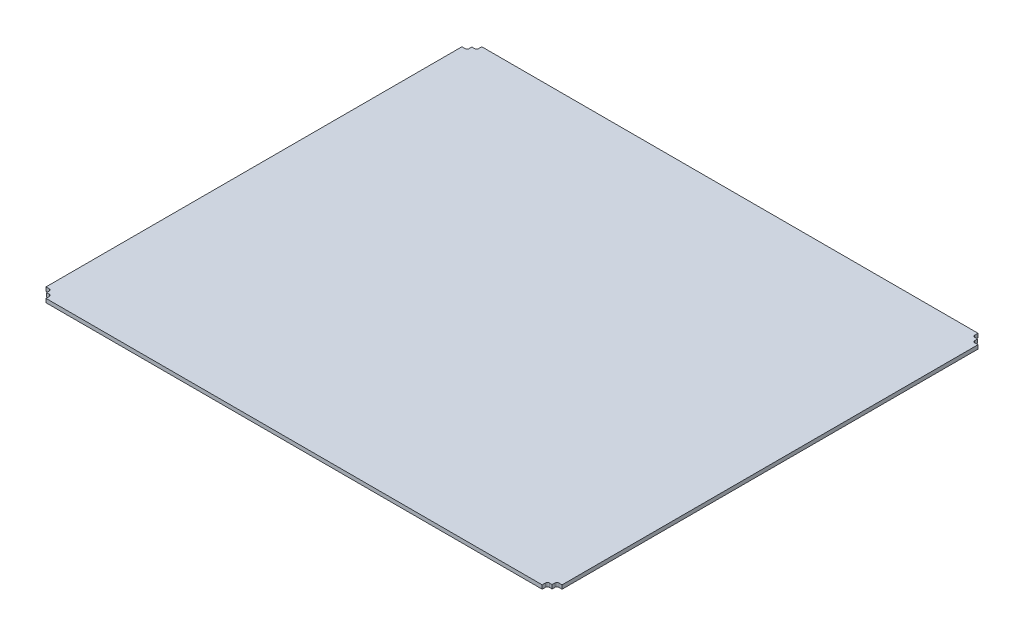
SolidWorks part; units mm, degrees
material "Acrylic (Medium-high impact)"
ref_plane "Front Plane" through (0, 0, 0) normal (0, 0, 1) x (1, 0, 0)
ref_plane "Top Plane" through (0, 0, 0) normal (0, 1, 0) x (1, 0, 0)
ref_plane "Right Plane" through (0, 0, 0) normal (1, 0, 0) x (0, 0, -1)
sketch "Sketch1" plane through (0, 0, 0) normal (0, 1, 0) x (1, 0, 0)
  line L1 (-428.625, -361.95) -> (428.625, -361.95)
  line L2 (-428.625, -361.95) -> (-428.625, 361.95)
  line L3 (-428.625, 361.95) -> (428.625, 361.95)
  line L4 (428.625, -361.95) -> (428.625, 361.95)
  line L5 (-428.625, -361.95) -> (428.625, 361.95) construction
  line L6 (-428.625, 361.95) -> (428.625, -361.95) construction
  point P0 (0, 0)
  dimension "D1" = 857.25
  dimension "D2" = 723.9
extrude "Boss-Extrude1" add sketch "Sketch1" along normal mid plane 6.35
sketch "Sketch2" plane through (0, 3.175, 0) normal (0, 1, 0) x (1, 0, 0)
  line L1 (-428.625, 361.95) -> (-412.115, 361.95)
  line L3 (-419.989, 353.314) -> (-415.29, 353.314)
  line L4 (-412.115, 361.95) -> (-412.115, 356.489)
  line L6 (-428.625, 361.95) -> (-428.625, 345.44)
  line L7 (-428.625, 345.44) -> (-423.164, 345.44)
  line L8 (-419.989, 353.314) -> (-419.989, 348.615)
  arc A0 (-415.29, 353.314) -> (-412.115, 356.489) centre (-415.29, 356.489) ccw
  arc A1 (-423.164, 345.44) -> (-419.989, 348.615) centre (-423.164, 348.615) ccw
  point P13 (-419.989, 345.44)
  dimension "D3" = 3.175
  dimension "D1" = 8.636
  dimension "D2" = 16.51
extrude "Cut-Extrude1" cut sketch "Sketch2" against normal through all
mirror "Mirror1" about plane through (0, 0, 0) normal (1, 0, 0) of "Cut-Extrude1"
mirror "Mirror2" about plane through (0, 0, 0) normal (0, 0, 1) of "Mirror1", "Cut-Extrude1"
